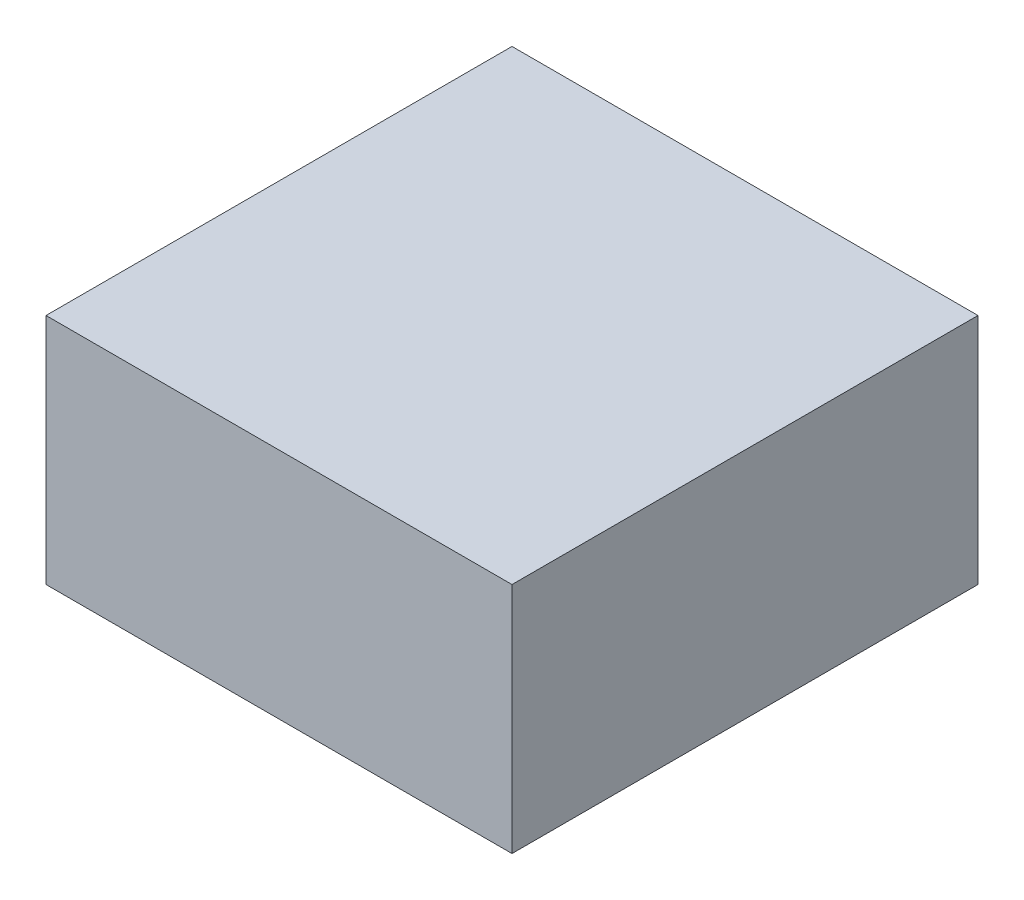
SolidWorks part; units mm, degrees
material "ABS PC"
ref_plane "Front Plane" through (0, 0, 0) normal (0, 0, 1) x (1, 0, 0)
ref_plane "Top Plane" through (0, 0, 0) normal (0, 1, 0) x (1, 0, 0)
ref_plane "Right Plane" through (0, 0, 0) normal (1, 0, 0) x (0, 0, -1)
sketch "Sketch1" plane through (0, 0, 0) normal (0, 1, 0) x (1, 0, 0)
  line L1 (-14.9065, -14.3111) -> (25.0935, -14.3111)
  line L2 (-14.9065, -14.3111) -> (-14.9065, 25.6889)
  line L3 (-14.9065, 25.6889) -> (25.0935, 25.6889)
  line L4 (25.0935, -14.3111) -> (25.0935, 25.6889)
  line L5 (-14.9065, -14.3111) -> (25.0935, 25.6889) construction
  line L6 (-14.9065, 25.6889) -> (25.0935, -14.3111) construction
  point P0 (5.0935, 5.6889)
  dimension "D1" = 40
  dimension "D2" = 40
extrude "Boss-Extrude1" add sketch "Sketch1" along normal blind 20
